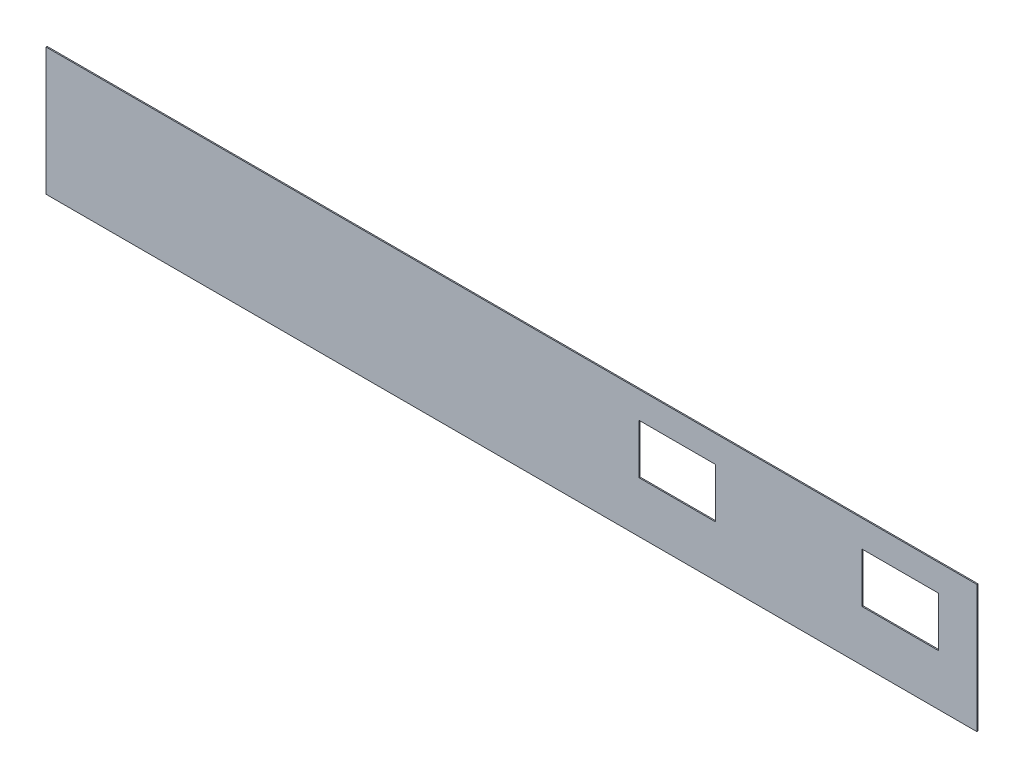
SolidWorks part; units mm, degrees
ref_plane "Front Plane" through (0, 0, 0) normal (0, 0, 1) x (1, 0, 0)
ref_plane "Top Plane" through (0, 0, 0) normal (0, 1, 0) x (1, 0, 0)
ref_plane "Right Plane" through (0, 0, 0) normal (1, 0, 0) x (0, 0, -1)
sketch "Sketch1" plane through (0, 0, 0) normal (0, 0, 1) x (1, 0, 0)
  line L0 (96, 0) -> (30, 0)
  line L1 (30, 0) -> (23, 0)
  line L2 (23, 0) -> (23, 10)
  line L3 (23, 10) -> (30, 10)
  line L4 (30, 10) -> (96, 10)
  line L5 (96, 10) -> (96, 0)
  line L6 (87, 4) -> (93, 4)
  line L7 (93, 4) -> (93, 7.9)
  line L8 (93, 7.9) -> (87, 7.9)
  line L9 (87, 7.9) -> (87, 4)
  line L10 (69.5, 4) -> (75.5, 4)
  line L11 (75.5, 4) -> (75.5, 7.9)
  line L12 (75.5, 7.9) -> (69.5, 7.9)
  line L13 (69.5, 7.9) -> (69.5, 4)
  dimension "D1" = 73
  dimension "D2" = 10
  dimension "D3" = 6
  dimension "D4" = 3.9
  dimension "D5" = 17.5
  dimension "D6" = 46.5
  dimension "D7" = 4
extrude "Boss-Extrude1" add sketch "Sketch1" along normal blind 0.09
